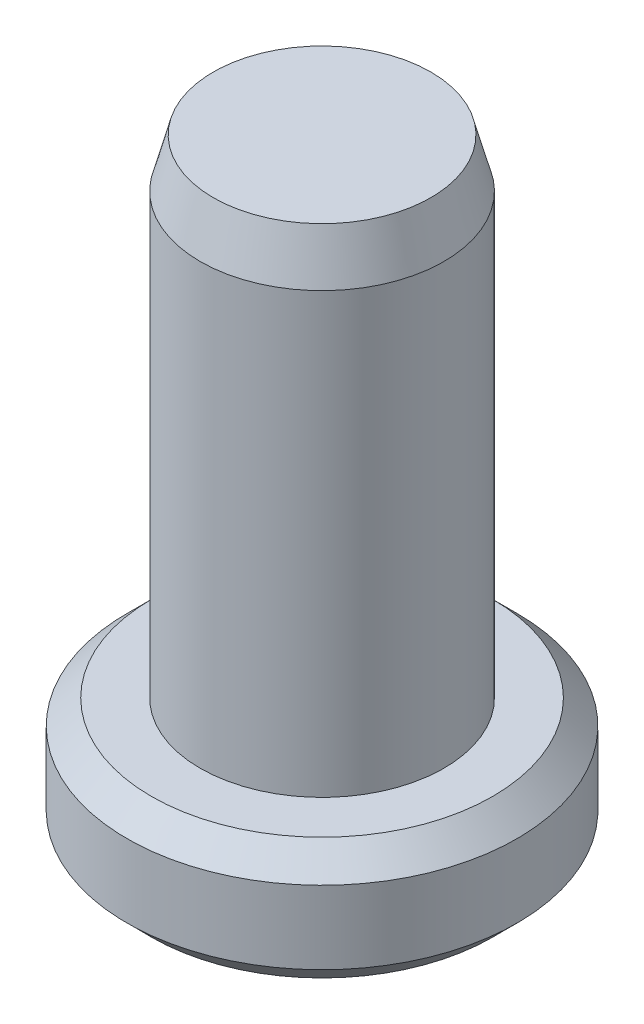
SolidWorks part; units mm, degrees
ref_plane "Front Plane" through (0, 0, 0) normal (0, 0, 1) x (1, 0, 0)
ref_plane "Top Plane" through (0, 0, 0) normal (0, 1, 0) x (1, 0, 0)
ref_plane "Right Plane" through (0, 0, 0) normal (1, 0, 0) x (0, 0, -1)
sketch "Sketch1" plane through (0, 0, 0) normal (0, 1, 0) x (1, 0, 0)
  circle A0 centre (0, 0) radius 5
  dimension "D1" = 10
extrude "Boss-Extrude1" add sketch "Sketch1" along normal blind 20
chamfer "Chamfer1" distance 2 angle 15 1 edges at (0, 20, 5)
sketch "Sketch2" plane through (0, 0, 0) normal (0, -1, 0) x (1, 0, 0)
  circle A0 centre (0, 0) radius 8
  dimension "D1" = 16
extrude "Boss-Extrude2" add sketch "Sketch2" along normal blind 5
chamfer "Chamfer2" distance 1 angle 45 2 edges at (0, -5, -8) (0, 0, -8)
